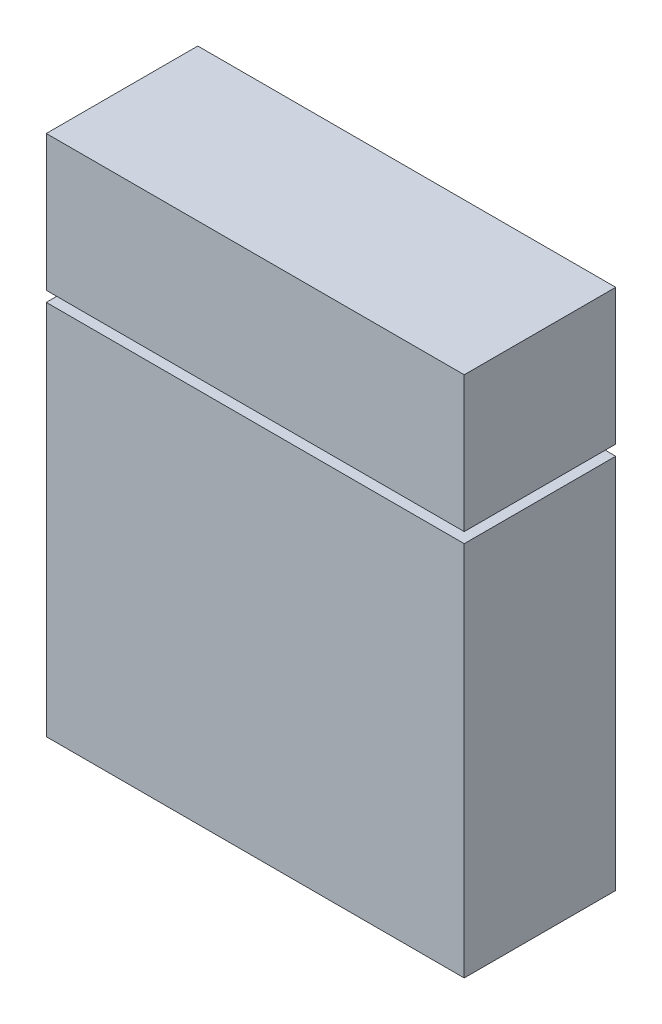
SolidWorks part; units mm, degrees
ref_plane "Front Plane" through (0, 0, 0) normal (0, 0, 1) x (1, 0, 0)
ref_plane "Top Plane" through (0, 0, 0) normal (0, 1, 0) x (1, 0, 0)
ref_plane "Right Plane" through (0, 0, 0) normal (1, 0, 0) x (0, 0, -1)
sketch "Sketch1" plane through (0, 0, 0) normal (0, 1, 0) x (1, 0, 0)
  line L1 (0, 0) -> (40, 0)
  line L2 (0, 0) -> (0, 14.5)
  line L3 (0, 14.5) -> (40, 14.5)
  line L4 (40, 0) -> (40, 14.5)
extrude "Boss-Extrude1" add sketch "Sketch1" along normal blind 36
shell "Shell1" thickness 2
sketch "Sketch3" plane through (0, 0, 0) normal (0, 0, 1) x (1, 0, 0)
  line L1 (0, 50) -> (40, 50)
  line L2 (0, 50) -> (0, 37)
  line L3 (0, 37) -> (40, 37)
  line L4 (40, 50) -> (40, 37)
  line L5 (0, 36) -> (40, 36) construction
  line L6 (0, 36) -> (0, 0) construction
  line L7 (40, 36) -> (40, 0) construction
extrude "Boss-Extrude3" add sketch "Sketch3" against normal up to surface (14.5 mm away) separate body contours L1 L4 L3 L2 up to face at (20, 18, -14.5)
shell "Shell2" thickness 1
sketch "Sketch2" plane through (0, 36, 0) normal (0, 1, 0) x (1, 0, 0)
  line L0 (1, 1) -> (1, 13.5)
  line L1 (2, 2) -> (38, 2)
  line L2 (2, 2) -> (2, 12.5)
  line L3 (2, 12.5) -> (38, 12.5)
  line L4 (38, 2) -> (38, 12.5)
  line L5 (1, 13.5) -> (39, 13.5)
  line L6 (39, 1) -> (39, 13.5)
  line L7 (1, 1) -> (39, 1)
  point P5 (38, 12.5)
  dimension "D1" = 1
extrude "Boss-Extrude2" add sketch "Sketch2" along normal blind 8
sketch "Sketch4" plane through (0, 0, -14.5) normal (0, 0, -1) x (-1, 0, 0)
  line L0 (-40, 25.9111) -> (0, 25.9111) construction
  line L1 (-40, 36) -> (-40, 0) construction
  line L2 (0, 36) -> (0, 0) construction
  text T0 "<b>X-ACTO</b>\r\n<b>#2</b>\r\n<b>QTY 60</b>" font "Atkinson Hyperlegible" height 5
  point P7 (0, 0)
  point P8 (0, 0)
extrude "Boss-Extrude4" add sketch "Sketch4" along normal blind 0.6
equation "\"D1@Sketch1\"=10.50mm + 4mm"
equation "\"D2@Sketch1\"=12mm*3+4mm"
equation "\"D1@Sketch3\"=49mm+1mm"
